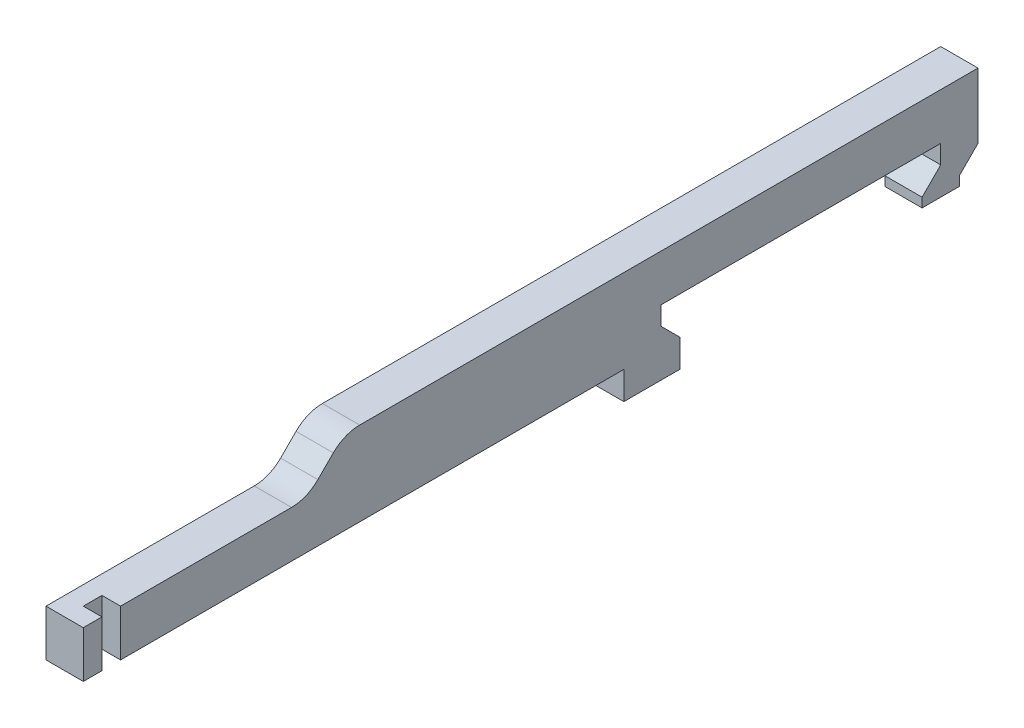
SolidWorks part; units mm, degrees
ref_plane "Спереди" through (0, 0, 0) normal (0, 0, 1) x (1, 0, 0)
ref_plane "Сверху" through (0, 0, 0) normal (0, 1, 0) x (1, 0, 0)
ref_plane "Справа" through (0, 0, 0) normal (1, 0, 0) x (0, 0, -1)
sketch "Эскиз1" plane through (0, 0, 0) normal (1, 0, 0) x (0, 0, -1)
  line L0 (12, 2.5) -> (14, 4.5)
  line L1 (0, 0) -> (12, 0)
  line L2 (0, 0) -> (0, 2.5)
  line L3 (0, 2.5) -> (12, 2.5)
  line L4 (12, 0) -> (12, 2.5)
  line L5 (14, 4.5) -> (14, 2.5) construction
  line L6 (14, 2.5) -> (12, 2.5) construction
  line L7 (14, 4.5) -> (29, 4.5)
  line L8 (12, 0) -> (29, 0)
  line L9 (29, 0) -> (29, -1.5)
  line L10 (29, -1.5) -> (32, -1.5)
  line L11 (32, -1.5) -> (32, 0)
  line L12 (32, 0) -> (31, 1)
  line L13 (31, 1) -> (31, 2)
  line L14 (31, 2) -> (46, 2)
  line L15 (32, 0) -> (31, 0) construction
  line L16 (31, 0) -> (31, 1) construction
  line L17 (38.5, 2) -> (38.5, 1) construction
  line L18 (45, 0) -> (46, 1)
  line L19 (46, 1) -> (46, 2)
  line L20 (45, 0) -> (45, -0.5)
  line L21 (45, -0.5) -> (47, -0.5)
  line L22 (47, -0.5) -> (47, 0)
  line L23 (47, 0) -> (48, 1)
  line L24 (48, 1) -> (48, 4.5)
  line L25 (48, 4.5) -> (29, 4.5)
  dimension "D1" = 2.5
  dimension "D2" = 12
  dimension "D3" = 2
  dimension "D4" = 2
  dimension "D5" = 15
  dimension "D6" = 17
  dimension "D7" = 1.5
  dimension "D8" = 3
  dimension "D9" = 1.5
  dimension "D10" = 1
  dimension "D11" = 1
  dimension "D12" = 1
  dimension "D13" = 15
  dimension "D14" = 0.5
  dimension "D15" = 2
extrude "Бобышка-Вытянуть1" add sketch "Эскиз1" along normal blind 2 contours L24 L25 L7 L0 L4 L8 L9 L10 L11 L12 L13 L14 L19 L18 L20 L21 L22 L23 | L1 L4 L3 L2
fillet "Скругление1" radius 2 2 edges at (1, 4.5, -14) (1, 2.5, -12)
sketch "Эскиз3" plane through (0, 2.5, 0) normal (0, 1, 0) x (1, 0, 0)
  line L0 (2, 0) -> (2, 1) construction
  line L1 (2, 0) -> (2, 11.1716) construction
  line L2 (2, 1) -> (1, 1)
  line L3 (1, 1) -> (1, 2)
  line L4 (1, 2) -> (2, 2)
  line L5 (2, 2) -> (2, 1)
  dimension "D1" = 1
  dimension "D2" = 1
  dimension "D3" = 1
extrude "Вырез-Вытянуть1" cut sketch "Эскиз3" against normal through all
